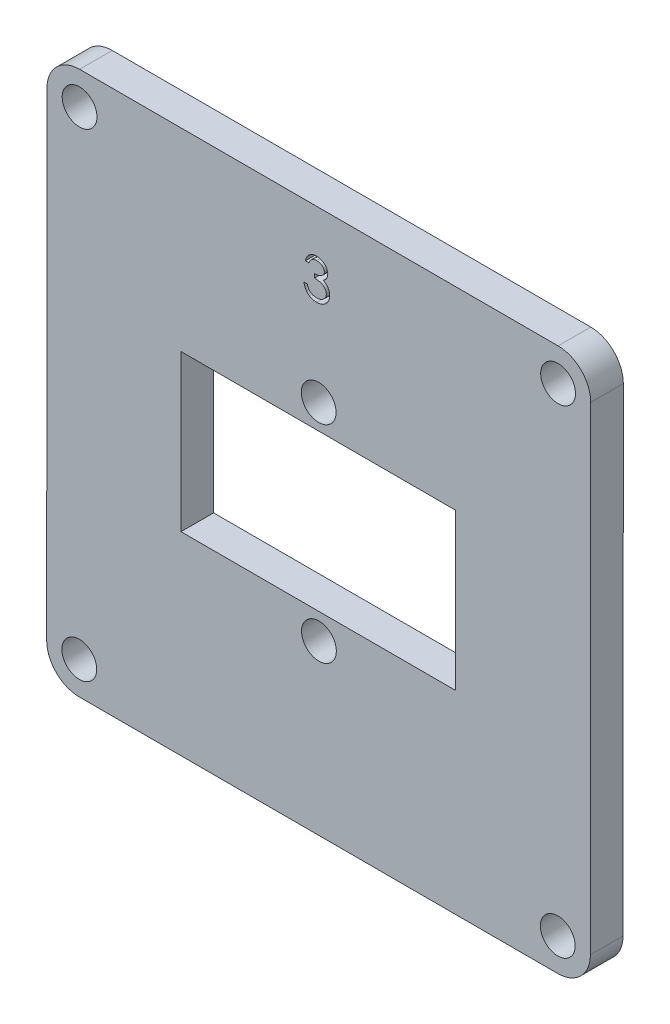
SolidWorks part; units mm, degrees
ref_plane "前视基准面" through (0, 0, 0) normal (0, 0, 1) x (1, 0, 0)
ref_plane "上视基准面" through (0, 0, 0) normal (0, 1, 0) x (1, 0, 0)
ref_plane "右视基准面" through (0, 0, 0) normal (1, 0, 0) x (0, 0, -1)
ref_plane "基准面4" through (0, 0, 3) normal (0, 0, 1) x (1, 0, 0)
sketch "草图1" plane through (0, 0, 3) normal (0, 0, 1) x (1, 0, 0)
  line L0 (291.1029, 60.8503) -> (291.0767, 16.8503)
  line L1 (294.0748, 13.8486) -> (338.0748, 13.8224)
  line L2 (341.0766, 16.8205) -> (341.1028, 60.8205)
  line L3 (338.1047, 63.8222) -> (294.1047, 63.8484)
  line L4 (303.4355, 46.0357) -> (328.6823, 46.0207)
  line L5 (328.6823, 46.0207) -> (328.6738, 31.6699)
  line L6 (328.6738, 31.6699) -> (303.4269, 31.685)
  line L7 (303.4269, 31.685) -> (303.4355, 46.0357)
  arc A0 (291.0767, 16.8503) -> (294.0748, 13.8486) centre (294.0766, 16.8485) ccw
  arc A1 (338.0748, 13.8224) -> (341.0766, 16.8205) centre (338.0766, 16.8223) ccw
  arc A2 (341.1028, 60.8205) -> (338.1047, 63.8222) centre (338.1029, 60.8223) ccw
  arc A3 (294.1047, 63.8484) -> (291.1029, 60.8503) centre (294.1029, 60.8485) ccw
  circle A4 centre (338.0766, 16.8223) radius 1.6
  circle A5 centre (294.1029, 60.8485) radius 1.6
  circle A6 centre (338.1029, 60.8223) radius 1.6
  circle A7 centre (294.0766, 16.8485) radius 1.6
  circle A8 centre (316.1112, 29.3157) radius 1.6
  circle A9 centre (316.0905, 48.3157) radius 1.6
  dimension "D1" = 19
  dimension "D2" = 44
  dimension "D3" = 44
extrude "凸台-拉伸1" add sketch "草图1" against normal blind 3
sketch "草图2" plane through (0, 0, 3) normal (0, 0, 1) x (1, 0, 0)
  text T0 "3\r\n"
extrude "切除-拉伸1" cut sketch "草图2" against normal blind 1
